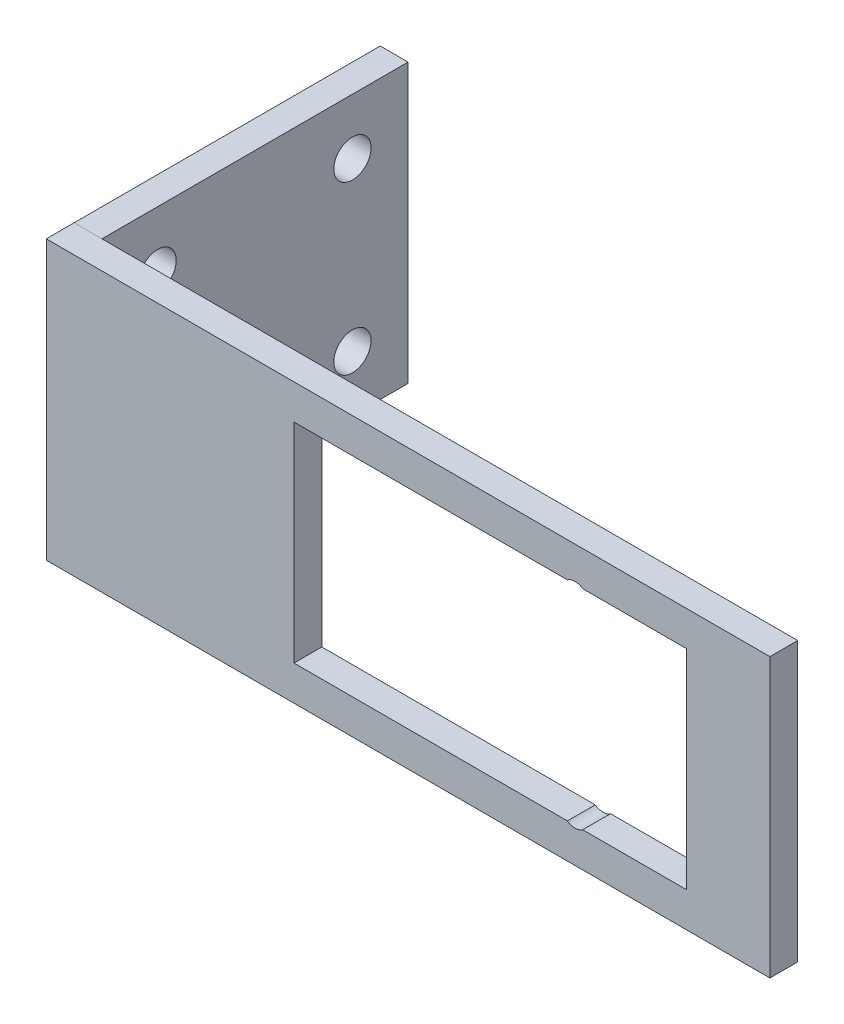
SolidWorks part; units mm, degrees
ref_plane "Front Plane" through (0, 0, 0) normal (0, 0, 1) x (1, 0, 0)
ref_plane "Top Plane" through (0, 0, 0) normal (0, 1, 0) x (1, 0, 0)
ref_plane "Right Plane" through (0, 0, 0) normal (1, 0, 0) x (0, 0, -1)
sketch "Sketch1" plane through (0, 0, 0) normal (1, 0, 0) x (0, 0, -1)
  line L0 (-31.8768, 23.0863) -> (-31.8768, -16.3439) construction
  line L2 (-44.5768, 4.0363) -> (-5.3691, 4.0363) construction
  line L4 (-45.8468, 16.7363) -> (-17.9068, 16.7363)
  line L5 (-40.7668, -3.5837) -> (-22.9868, -3.5837) construction
  line L6 (-40.7668, -3.5837) -> (-40.7668, 11.6563) construction
  line L7 (-40.7668, 11.6563) -> (-22.9868, 11.6563) construction
  line L8 (-22.9868, -3.5837) -> (-22.9868, 11.6563) construction
  line L9 (-40.7668, -3.5837) -> (-22.9868, 11.6563) construction
  line L10 (-40.7668, 11.6563) -> (-22.9868, -3.5837) construction
  line L11 (-17.9068, -8.6637) -> (-17.9068, 16.7363)
  line L12 (-45.8468, -8.6637) -> (-17.9068, -8.6637)
  line L13 (-45.8468, -8.6637) -> (-45.8468, 16.7363)
  point P17 (-31.8768, 4.0363)
  dimension "D1" = 5.08
extrude "side connecting to grip" add sketch "Sketch1" along normal blind 2.54 separate body
hole_wizard "M3 Clearance Hole1" positions "Sketch4" profile "Sketch5" hole size "M3" standard "ANSI Metric" end condition through all
sketch "Sketch4" plane through (2.54, 0, 0) normal (1, 0, 0) x (0, 0, -1)
  point P0 (-40.7668, 11.6563)
  point P3 (-22.9868, 11.6563)
  point P6 (-22.9868, -3.5837)
  point P9 (-40.7668, -3.5837)
sketch "Sketch5" plane through (2.54, 11.6563, 40.7668) normal (0, 1, 0) x (0, 0, -1)
  line L0 (0, 0) -> (0, 2.54)
  line L1 (0, 2.54) -> (1.7, 2.54)
  line L2 (1.7, 2.54) -> (1.7, 0)
  line L5 (1.7, 0) -> (0, 0)
  line L11 (0, -6.35) -> (0, 107.95) construction
  dimension "Thru Hole Dia." = 3.4
  dimension "Thru Hole Depth" = 2.54
sketch "Sketch6" plane through (2.54, 0, 0) normal (1, 0, 0) x (0, 0, -1)
  line L42 (-45.8468, 16.7363) -> (-48.3868, 16.7363)
  line L43 (-48.3868, 16.7363) -> (-48.3868, -8.6637)
  line L44 (-48.3868, -8.6637) -> (-45.8468, -8.6637)
  line L45 (-45.8468, -8.6637) -> (-45.8468, 16.7363) construction
  line L46 (-45.8468, 16.7363) -> (-45.8468, -8.6637)
  dimension "D1" = 2.54
extrude "side connecting to servo" add sketch "Sketch6" along normal blind 63.5 and the other way blind 2.54 separate body
sketch "servo holes" plane through (0, 0, 48.3868) normal (0, 0, 1) x (1, 0, 0)
  line L0 (0, 4.0363) -> (36.6866, 4.0363) construction
  circle A0 centre (48.26, 4.0363) radius 8.55 construction
  point P5 (48.26, -4.5137)
  point P8 (48.26, 12.5863)
hole_wizard "cutout servo holes" positions "Sketch8" profile "Sketch9" hole size "M2" standard "ANSI Metric" end condition through all
sketch "Sketch8" plane through (0, 0, 48.3868) normal (0, 0, 1) x (1, 0, 0)
  point P0 (48.26, 12.5863)
  point P3 (48.26, -4.5137)
sketch "Sketch9" plane through (48.26, 12.5863, 48.3868) normal (1, 0, 0) x (0, -1, 0)
  line L0 (0, 0) -> (0, 30.48)
  line L1 (0, 30.48) -> (1.2, 30.48)
  line L2 (1.2, 30.48) -> (1.2, 0)
  line L5 (1.2, 0) -> (0, 0)
  line L11 (0, -6.35) -> (0, 107.95) construction
  dimension "Thru Hole Dia." = 2.4
  dimension "Thru Hole Depth" = 30.48
sketch "Sketch10" plane through (0, 0, 48.3868) normal (0, 0, 1) x (1, 0, 0)
  line L1 (22.606, 13.5613) -> (58.42, 13.5613)
  line L2 (22.606, 13.5613) -> (22.606, -5.4887)
  line L3 (22.606, -5.4887) -> (58.42, -5.4887)
  line L4 (58.42, 13.5613) -> (58.42, -5.4887)
  line L5 (66.04, 16.7363) -> (66.04, -8.6637) construction
  line L7 (0, 4.0363) -> (36.6866, 4.0363) construction
  point P4 (22.606, 4.0363)
  dimension "D1" = 35.814
  dimension "D2" = 19.05
  dimension "D3" = 7.62
  dimension "D4" = 10.16
extrude "Cut-Extrude1" cut sketch "Sketch10" against normal blind 2.54
